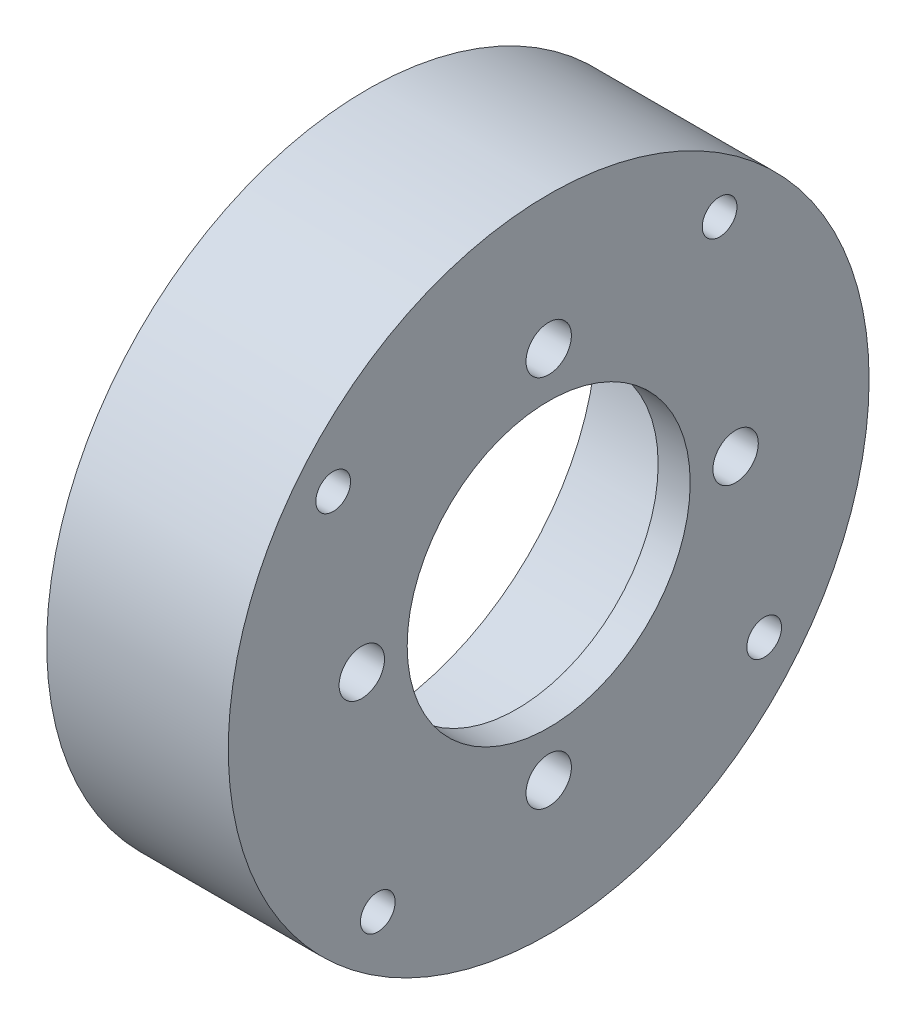
SolidWorks part; units mm, degrees
ref_plane "Front Plane" through (0, 0, 0) normal (0, 0, 1) x (1, 0, 0)
ref_plane "Top Plane" through (0, 0, 0) normal (0, 1, 0) x (1, 0, 0)
ref_plane "Right Plane" through (0, 0, 0) normal (1, 0, 0) x (0, 0, -1)
sketch "Sketch1" plane through (0, 0, 0) normal (1, 0, 0) x (0, 0, -1)
  circle A0 centre (0, 0) radius 21.5
  circle A1 centre (0, 0) radius 30
  dimension "D1" = 43
  dimension "D2" = 60
extrude "Boss-Extrude1" add sketch "Sketch1" along normal blind 14
sketch "Sketch2" plane through (14, 0, 0) normal (1, 0, 0) x (0, 0, -1)
  circle A0 centre (0, 0) radius 30
  circle A1 centre (0, 17.5) radius 2.125
  circle A2 centre (17.5, 0) radius 2.125
  circle A3 centre (0, -17.5) radius 2.125
  circle A4 centre (-17.5, 0) radius 2.125
  circle A5 centre (0, 0) radius 13.25
  point P14 (0, 0)
  dimension "D2" = 4.25
  dimension "D4" = 26.5
  dimension "D1" = 17.5
  dimension "D3" = 4
extrude "Boss-Extrude2" add sketch "Sketch2" along normal blind 3
sketch "Sketch4" plane through (17, 0, 0) normal (1, 0, 0) x (0, 0, -1)
  circle A0 centre (0, 0) radius 25.75 construction
  circle A1 centre (-20.1758, 16) radius 1.625
  circle A2 centre (16, 20.1758) radius 1.625
  circle A3 centre (20.1758, -16) radius 1.625
  circle A4 centre (-16, -20.1758) radius 1.625
  point P14 (0, 0)
  dimension "D1" = 51.5
  dimension "D3" = 3.25
  dimension "D2" = 16
  dimension "D4" = 4
extrude "Cut-Extrude1" cut sketch "Sketch4" against normal through all
